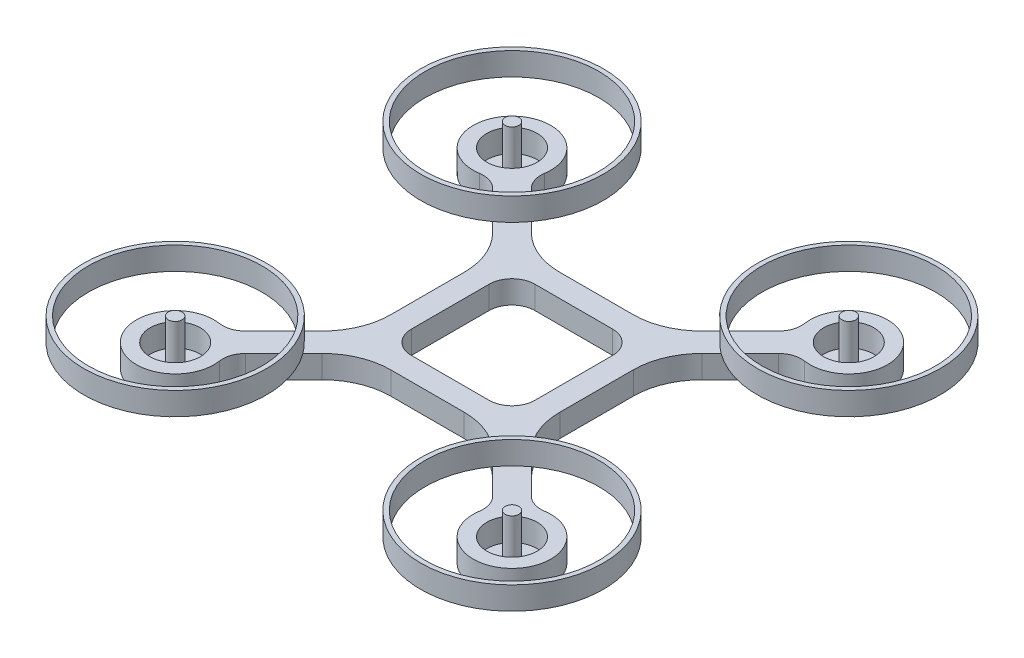
SolidWorks part; units mm, degrees
ref_plane "Front Plane" through (0, 0, 0) normal (0, 0, 1) x (1, 0, 0)
ref_plane "Top Plane" through (0, 0, 0) normal (0, 1, 0) x (1, 0, 0)
ref_plane "Right Plane" through (0, 0, 0) normal (1, 0, 0) x (0, 0, -1)
sketch "Sketch1" plane through (0, 0, 0) normal (0, 1, 0) x (1, 0, 0)
  line L0 (0, 0) -> (-41.4525, -41.4525) construction
  line L1 (8.0442, 18.5) -> (-8.0442, 18.5)
  line L2 (18.5, 8.0442) -> (18.5, -8.0442)
  line L3 (8.0442, -18.5) -> (-8.0442, -18.5)
  line L4 (-18.5, 8.0442) -> (-18.5, -8.0442)
  line L5 (18.5, 18.5) -> (-18.5, -18.5) construction
  line L6 (18.5, -18.5) -> (-18.5, 18.5) construction
  line L7 (8.5126, 13.5126) -> (-8.5126, 13.5126)
  line L8 (13.5126, 8.5126) -> (13.5126, -8.5126)
  line L9 (8.5126, -13.5126) -> (-8.5126, -13.5126)
  line L10 (-13.5126, 8.5126) -> (-13.5126, -8.5126)
  line L11 (13.5126, 13.5126) -> (-13.5126, -13.5126) construction
  line L12 (13.5126, -13.5126) -> (-13.5126, 13.5126) construction
  line L13 (0, 0) -> (43.9038, 43.9038) construction
  line L19 (36.8665, 36.8665) -> (-36.8665, -36.8665) construction
  line L20 (36.8665, -36.8665) -> (-36.8665, 36.8665) construction
  line L22 (-22.8934, -18.6508) -> (-31.2956, -27.0529)
  line L24 (-18.6508, -22.8934) -> (-27.0529, -31.2956)
  line L32 (-22.8934, 18.6508) -> (-31.2956, 27.0529)
  line L33 (-18.6508, 22.8934) -> (-27.0529, 31.2956)
  line L34 (22.8934, -18.6508) -> (31.2956, -27.0529)
  line L35 (18.6508, -22.8934) -> (27.0529, -31.2956)
  line L36 (22.8934, 18.6508) -> (31.2956, 27.0529)
  line L37 (18.6508, 22.8934) -> (27.0529, 31.2956)
  arc A0 (8.5126, 13.5126) -> (13.5126, 8.5126) centre (8.5126, 8.5126) cw
  arc A1 (13.5126, -8.5126) -> (8.5126, -13.5126) centre (8.5126, -8.5126) cw
  arc A2 (-8.5126, -13.5126) -> (-13.5126, -8.5126) centre (-8.5126, -8.5126) cw
  arc A3 (-13.5126, 8.5126) -> (-8.5126, 13.5126) centre (-8.5126, 8.5126) cw
  arc A8 (35.5838, 28.4604) -> (28.4604, 35.5838) centre (36.8635, 36.8635) ccw
  circle A9 centre (36.8635, 36.8635) radius 5.5
  arc A12 (27.0529, 31.2956) -> (28.4604, 35.5838) centre (23.5174, 34.8311) ccw
  arc A13 (31.2956, 27.0529) -> (35.5838, 28.4604) centre (34.8311, 23.5174) cw
  arc A16 (28.4604, -35.5838) -> (35.5838, -28.4604) centre (36.8635, -36.8635) ccw
  circle A17 centre (36.8635, -36.8635) radius 5.5
  arc A18 (27.0529, -31.2956) -> (28.4604, -35.5838) centre (23.5174, -34.8311) cw
  arc A19 (31.2956, -27.0529) -> (35.5838, -28.4604) centre (34.8311, -23.5174) ccw
  arc A20 (-35.5838, -28.4604) -> (-28.4604, -35.5838) centre (-36.8635, -36.8635) ccw
  circle A21 centre (-36.8635, -36.8635) radius 5.5
  arc A22 (-31.2956, -27.0529) -> (-35.5838, -28.4604) centre (-34.8311, -23.5174) cw
  arc A23 (-27.0529, -31.2956) -> (-28.4604, -35.5838) centre (-23.5174, -34.8311) ccw
  arc A24 (-28.4604, 35.5838) -> (-35.5838, 28.4604) centre (-36.8635, 36.8635) ccw
  circle A25 centre (-36.8635, 36.8635) radius 5.5
  arc A26 (-27.0529, 31.2956) -> (-28.4604, 35.5838) centre (-23.5174, 34.8311) cw
  arc A27 (-31.2956, 27.0529) -> (-35.5838, 28.4604) centre (-34.8311, 23.5174) ccw
  arc A28 (-18.5, -8.0442) -> (-22.8934, -18.6508) centre (-33.5, -8.0442) cw
  arc A29 (-8.0442, -18.5) -> (-18.6508, -22.8934) centre (-8.0442, -33.5) ccw
  arc A30 (8.0442, -18.5) -> (18.6508, -22.8934) centre (8.0442, -33.5) cw
  arc A31 (18.5, -8.0442) -> (22.8934, -18.6508) centre (33.5, -8.0442) ccw
  arc A32 (18.5, 8.0442) -> (22.8934, 18.6508) centre (33.5, 8.0442) cw
  arc A33 (8.0442, 18.5) -> (18.6508, 22.8934) centre (8.0442, 33.5) ccw
  arc A34 (-18.5, 8.0442) -> (-22.8934, 18.6508) centre (-33.5, 8.0442) ccw
  arc A35 (-8.0442, 18.5) -> (-18.6508, 22.8934) centre (-8.0442, 33.5) cw
  point P0 (0, 0)
  point P6 (0, 0)
  point P33 (2.1213, -2.1213)
  point P34 (46.0252, 41.7825)
  point P43 (-2.1213, 2.1213)
  point P44 (41.7825, 46.0252)
  point P82 (0, 0)
  point P87 (-18.5, -14.2574)
  point P90 (-14.2574, -18.5)
  point P93 (14.2574, -18.5)
  point P96 (18.5, -14.2574)
  point P99 (18.5, 14.2574)
  point P102 (14.2574, 18.5)
  point P105 (-18.5, 14.2574)
  point P108 (-14.2574, 18.5)
  dimension "D3" = 5
  dimension "D4" = 4
  dimension "D10" = 5
  dimension "D6" = 15
  dimension "D1" = 37
  dimension "D2" = 37
  dimension "D5" = 73.733
extrude "Boss-Extrude2" add sketch "Sketch1" along normal blind 5
sketch "Sketch3" plane through (0, 5, 0) normal (0, 1, 0) x (1, 0, 0)
  circle A0 centre (36.8635, -36.8635) radius 20
  circle A1 centre (36.8635, -36.8635) radius 19
extrude "Boss-Extrude4" add sketch "Sketch3" along normal blind 5
pattern_linear "LPattern1" count 2 spacing 73.73 along (0, 0, -1) count 2 spacing 73.73 along (-1, 0, 0) of "Boss-Extrude4"
sketch "Sketch4" plane through (0, 0, 0) normal (0, -1, 0) x (1, 0, 0)
  circle A0 centre (-36.8635, 36.8635) radius 5.5
  circle A1 centre (36.8665, 36.8635) radius 5.5
  circle A2 centre (36.8665, -36.8665) radius 5.5
  circle A3 centre (-36.8635, -36.8665) radius 5.5
  dimension "D1" = 2
  dimension "D2" = 2
extrude "Boss-Extrude5" add sketch "Sketch4" along normal blind 2
sketch "Sketch5" plane through (0, 0, 0) normal (0, 1, 0) x (1, 0, 0)
  circle A0 centre (36.8635, -36.8635) radius 1.5
extrude "Boss-Extrude6" add sketch "Sketch5" along normal blind 10
pattern_linear "LPattern2" count 2 spacing 73.73 along (-1, 0, 0) count 2 spacing 73.73 along (0, 0, -1) of "Boss-Extrude6"
